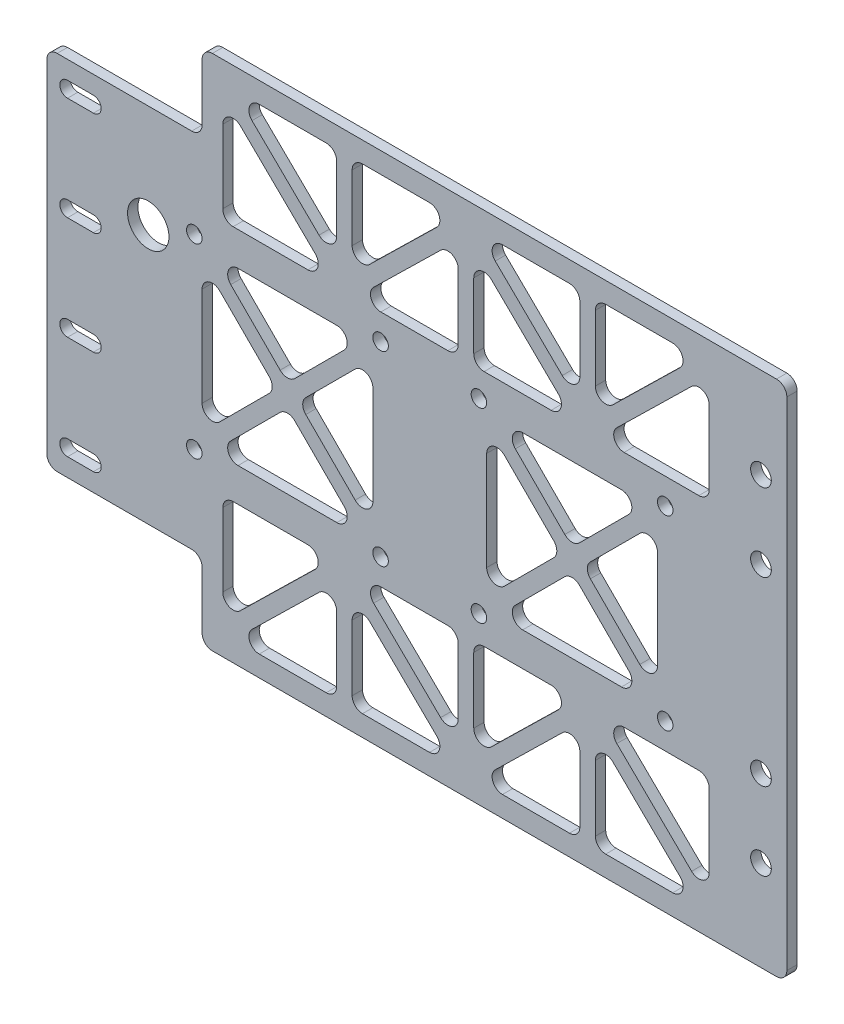
SolidWorks part; units mm, degrees
material "Thornel Mat VMA"
ref_plane "前视基准面" through (0, 0, 0) normal (0, 0, 1) x (1, 0, 0)
ref_plane "上视基准面" through (0, 0, 0) normal (0, 1, 0) x (1, 0, 0)
ref_plane "右视基准面" through (0, 0, 0) normal (1, 0, 0) x (0, 0, -1)
other "Configuration Table"
sketch "草图1" plane through (0, 0, 0) normal (0, 0, 1) x (1, 0, 0)
  line L1 (-71.5, -50) -> (71.5, -50)
  line L2 (-71.5, -50) -> (-71.5, 50)
  line L3 (-71.5, 50) -> (71.5, 50)
  line L4 (71.5, -50) -> (71.5, 50)
  line L5 (-71.5, -50) -> (71.5, 50) construction
  line L6 (-71.5, 50) -> (71.5, -50) construction
  point P0 (0, 0)
  dimension "D1" = 100
  dimension "D2" = 143
extrude "凸台-拉伸1" add sketch "草图1" along normal blind 2
sketch "草图2" plane through (0, 0, 2) normal (0, 0, 1) x (1, 0, 0)
  line L0 (66.5, 50) -> (66.5, 32.5) construction
  line L1 (71.5, 50) -> (-71.5, 50) construction
  line L2 (66.5, 32.5) -> (66.5, 17.5) construction
  line L3 (0, 0) -> (86.4938, 0) construction
  line L4 (71.5, -50) -> (71.5, 50) construction
  line L5 (66.5, -32.5) -> (66.5, -17.5) construction
  line L6 (0, 0) -> (-95.2784, 0) construction
  line L7 (-67.5, 50) -> (-67.5, 30) construction
  line L8 (-67.5, 30) -> (-67.5, 10) construction
  line L9 (-67.5, 10) -> (-62.5, 10) construction
  line L10 (-67.5, 11.5) -> (-62.5, 11.5)
  line L11 (-67.5, 8.5) -> (-62.5, 8.5)
  line L12 (-71.5, 50) -> (-71.5, -50) construction
  line L13 (-67.5, 30) -> (-62.5, 30) construction
  line L14 (-67.5, 31.5) -> (-62.5, 31.5)
  line L15 (-67.5, 28.5) -> (-62.5, 28.5)
  line L16 (-67.5, -30) -> (-67.5, -10) construction
  line L17 (-67.5, -30) -> (-62.5, -30) construction
  line L18 (-67.5, -31.5) -> (-62.5, -31.5)
  line L19 (-67.5, -28.5) -> (-62.5, -28.5)
  line L20 (-67.5, -10) -> (-62.5, -10) construction
  line L21 (-67.5, -11.5) -> (-62.5, -11.5)
  line L22 (-67.5, -8.5) -> (-62.5, -8.5)
  circle A0 centre (66.5, 32.5) radius 2
  circle A1 centre (66.5, 17.5) radius 2
  circle A2 centre (66.5, -17.5) radius 2
  circle A3 centre (66.5, -32.5) radius 2
  arc A4 (-67.5, 11.5) -> (-67.5, 8.5) centre (-67.5, 10) ccw
  arc A5 (-62.5, 8.5) -> (-62.5, 11.5) centre (-62.5, 10) ccw
  arc A6 (-67.5, 31.5) -> (-67.5, 28.5) centre (-67.5, 30) ccw
  arc A7 (-62.5, 28.5) -> (-62.5, 31.5) centre (-62.5, 30) ccw
  arc A8 (-67.5, -31.5) -> (-67.5, -28.5) centre (-67.5, -30) cw
  arc A9 (-62.5, -28.5) -> (-62.5, -31.5) centre (-62.5, -30) cw
  arc A10 (-67.5, -11.5) -> (-67.5, -8.5) centre (-67.5, -10) cw
  arc A11 (-62.5, -8.5) -> (-62.5, -11.5) centre (-62.5, -10) cw
  point P19 (-65, 10)
  point P28 (-65, 30)
  point P37 (-65, -30)
  point P43 (-65, -10)
  dimension "D4" = 4
  dimension "D7" = 1.5
  dimension "D1" = 17.5
  dimension "D2" = 15
  dimension "D3" = 5
  dimension "D5" = 20
  dimension "D6" = 10
  dimension "D8" = 5
  dimension "D9" = 4
  dimension "D10" = 5
extrude "切除-拉伸1" cut sketch "草图2" against normal up to surface (2 mm away) up to face at (0, 0, 0)
sketch "草图3" plane through (0, 0, 2) normal (0, 0, 1) x (1, 0, 0)
  line L0 (0, 0) -> (30, 0) construction
  line L1 (0, 0) -> (-25, 0) construction
  line L3 (12, -18) -> (48, -18) construction
  line L4 (12, -18) -> (12, 18) construction
  line L5 (12, 18) -> (48, 18) construction
  line L6 (48, -18) -> (48, 18) construction
  line L7 (12, -18) -> (48, 18) construction
  line L8 (12, 18) -> (48, -18) construction
  line L9 (-43, -18) -> (-7, -18) construction
  line L10 (-43, -18) -> (-43, 18) construction
  line L11 (-43, 18) -> (-7, 18) construction
  line L12 (-7, -18) -> (-7, 18) construction
  line L13 (-43, -18) -> (-7, 18) construction
  line L14 (-43, 18) -> (-7, -18) construction
  circle A0 centre (66.5, -17.5) radius 2 construction
  circle A1 centre (48, 18) radius 1.5
  circle A2 centre (48, -18) radius 1.5
  circle A3 centre (12, -18) radius 1.5
  circle A4 centre (12, 18) radius 1.5
  circle A5 centre (-7, 18) radius 1.5
  circle A6 centre (-7, -18) radius 1.5
  circle A7 centre (-43, -18) radius 1.5
  circle A8 centre (-43, 18) radius 1.5
  dimension "D4" = 3
  dimension "D1" = 18.5
  dimension "D2" = 19
  dimension "D3" = 36
extrude "切除-拉伸2" cut sketch "草图3" against normal up to surface (2 mm away) up to face at (-65, 10, 0)
sketch "草图4" plane through (0, 0, 2) normal (0, 0, 1) x (1, 0, 0)
  line L1 (-71.5, 50) -> (-41.5, 50)
  line L2 (-71.5, 50) -> (-71.5, 35)
  line L3 (-71.5, 35) -> (-41.5, 35)
  line L4 (-41.5, 50) -> (-41.5, 35)
  line L5 (-71.5, -50) -> (-41.5, -50)
  line L6 (-71.5, -50) -> (-71.5, -35)
  line L7 (-71.5, -35) -> (-41.5, -35)
  line L8 (-41.5, -50) -> (-41.5, -35)
  dimension "D1" = 30
  dimension "D2" = 15
extrude "切除-拉伸3" cut sketch "草图4" against normal up to surface (2 mm away) up to face at (46.5, -18, 0)
sketch "草图5" plane through (0, 0, 2) normal (0, 0, 1) x (1, 0, 0)
  line L0 (-43, 18) -> (-7, -18) construction
  line L1 (-7, -18) -> (-43, -18) construction
  line L2 (-43, -18) -> (-7, 18) construction
  line L3 (-7, 18) -> (-43, 18) construction
  line L4 (0, 0) -> (98.3123, 0) construction
  line L5 (-37.5, 46) -> (56.5, 46)
  line L6 (-37.5, 46) -> (-37.5, 23)
  line L7 (-37.5, 23) -> (56.5, 23)
  line L8 (56.5, 46) -> (56.5, 23)
  line L9 (-39.3787, 16.5) -> (-25, 2.1213)
  line L10 (-25, 2.1213) -> (-10.6213, 16.5)
  line L11 (-10.6213, 16.5) -> (-39.3787, 16.5)
  line L12 (-41.5, 35) -> (-41.5, 50) construction
  line L13 (71.5, 50) -> (-41.5, 50) construction
  line L14 (71.5, -50) -> (71.5, 50) construction
  line L15 (56.5, 46) -> (33, 23) construction
  line L16 (33, 23) -> (9.5, 46) construction
  line L17 (9.5, 46) -> (-14, 23) construction
  line L18 (-14, 23) -> (-37.5, 46) construction
  line L19 (-37.5, 43.9011) -> (-16.1445, 23)
  line L20 (-35.3555, 46) -> (-14, 25.0989)
  line L21 (-14, 25.0989) -> (7.3555, 46)
  line L22 (-11.8555, 23) -> (9.5, 43.9011)
  line L23 (9.5, 43.9011) -> (30.8555, 23)
  line L24 (11.6445, 46) -> (33, 25.0989)
  line L25 (33, 25.0989) -> (54.3555, 46)
  line L26 (35.1445, 23) -> (56.5, 43.9011)
  line L27 (-15.5, 23) -> (-15.5, 46)
  line L28 (-14, 23) -> (-14, 46) construction
  line L29 (-12.5, 23) -> (-12.5, 46)
  line L30 (9.5, 46) -> (9.5, 23) construction
  line L31 (8, 46) -> (8, 23)
  line L32 (11, 46) -> (11, 23)
  line L33 (34.5, 23) -> (34.5, 46)
  line L34 (31.5, 23) -> (31.5, 46)
  line L35 (-41.5, -14.3787) -> (-41.5, 14.3787)
  line L36 (-41.5, 14.3787) -> (-27.1213, 0)
  line L37 (-27.1213, 0) -> (-41.5, -14.3787)
  line L38 (-25, -2.1213) -> (-39.3787, -16.5)
  line L39 (-39.3787, -16.5) -> (-10.6213, -16.5)
  line L40 (-8.5, -14.3787) -> (-22.8787, 0)
  line L41 (-10.6213, -16.5) -> (-25, -2.1213)
  line L42 (-22.8787, 0) -> (-8.5, 14.3787)
  line L43 (-8.5, 14.3787) -> (-8.5, -14.3787)
  line L44 (-7, 18) -> (12, 18) construction
  line L45 (2.5, 18) -> (2.5, -26.3932) construction
  line L46 (48, -18) -> (12, 18) construction
  line L47 (12, -18) -> (48, -18) construction
  line L48 (13.5, 14.3787) -> (13.5, -14.3787)
  line L49 (27.8787, 0) -> (13.5, 14.3787)
  line L50 (15.6213, -16.5) -> (30, -2.1213)
  line L51 (13.5, -14.3787) -> (27.8787, 0)
  line L52 (44.3787, -16.5) -> (15.6213, -16.5)
  line L53 (30, -2.1213) -> (44.3787, -16.5)
  line L54 (32.1213, 0) -> (46.5, -14.3787)
  line L55 (46.5, 14.3787) -> (32.1213, 0)
  line L56 (46.5, -14.3787) -> (46.5, 14.3787)
  line L57 (15.6213, 16.5) -> (44.3787, 16.5)
  line L58 (30, 2.1213) -> (15.6213, 16.5)
  line L59 (44.3787, 16.5) -> (30, 2.1213)
  line L60 (9.5, -46) -> (9.5, -23) construction
  line L61 (-14, -23) -> (-14, -46) construction
  line L62 (-14, -23) -> (-37.5, -46) construction
  line L63 (9.5, -46) -> (-14, -23) construction
  line L64 (33, -23) -> (9.5, -46) construction
  line L65 (56.5, -46) -> (33, -23) construction
  line L66 (31.5, -23) -> (31.5, -46)
  line L67 (34.5, -23) -> (34.5, -46)
  line L68 (11, -46) -> (11, -23)
  line L69 (8, -46) -> (8, -23)
  line L70 (-12.5, -23) -> (-12.5, -46)
  line L71 (-15.5, -23) -> (-15.5, -46)
  line L72 (35.1445, -23) -> (56.5, -43.9011)
  line L73 (33, -25.0989) -> (54.3555, -46)
  line L74 (11.6445, -46) -> (33, -25.0989)
  line L75 (9.5, -43.9011) -> (30.8555, -23)
  line L76 (-11.8555, -23) -> (9.5, -43.9011)
  line L77 (-14, -25.0989) -> (7.3555, -46)
  line L78 (-35.3555, -46) -> (-14, -25.0989)
  line L79 (-37.5, -43.9011) -> (-16.1445, -23)
  line L80 (56.5, -46) -> (56.5, -23)
  line L81 (-37.5, -23) -> (56.5, -23)
  line L82 (-37.5, -46) -> (-37.5, -23)
  line L83 (-37.5, -46) -> (56.5, -46)
  circle A0 centre (-7, 18) radius 1.5 construction
  dimension "D1" = 1.5
  dimension "D2" = 1.5
  dimension "D3" = 1.5
  dimension "D4" = 4
  dimension "D5" = 4
  dimension "D6" = 15
  dimension "D7" = 5
  dimension "D8" = 1.5
  dimension "D9" = 1.5
  dimension "D10" = 1.5
  dimension "D11" = 3
  dimension "D12" = 1.5
  dimension "D13" = 1.5
  dimension "D14" = 1.5
  dimension "D15" = 1.5
  dimension "D16" = 1.5
extrude "切除-拉伸4" cut sketch "草图5" against normal blind 2 contours L37 L36 L35 | L10 L11 L9 | L43 L42 L40 | L39 L41 L38 | L48 L51 L49 | L59 L57 L58 | L54 L56 L55 | L53 L50 L52 | L81 L72 L80 | L67 L83 L73 | L74 L83 L66 | L81 L68 L75 | L81 L76 L69 | L70 L83 L77 | L78 L83 L71 | L82 L79 L81 | L19 L6 L7 | L20 L27 L5 | L29 L21 L5 | L31 L22 L7 | L23 L32 L7 | L24 L34 L5 | L33 L25 L5 | L26 L7 L8
sketch "草图6" plane through (0, 0, 2) normal (0, 0, 1) x (1, 0, 0)
  line L1 (-71.5, 35) -> (-41.5, 35) construction
  line L2 (-71.5, 35) -> (-71.5, -35) construction
  circle A0 centre (-51.9, 15.1) radius 4
  dimension "D2" = 8
  dimension "D1" = 19.9
  dimension "D3" = 19.6
extrude "切除-拉伸5" cut sketch "草图6" against normal blind 10
fillet "圆角1" radius 2 80 edges at (8, -42.433, 1) (-11.8555, -23, 1) (8, -23, 1) (11, -42.433, 1) (11, -23, 1) (30.8555, -23, 1) (31.5, -46, 1) (11.6445, -46, 1) (31.5, -26.567, 1) (-37.5, 43.9011, 1) (-16.1445, 23, 1) (-16.1445, -23, 1) (-37.5, -43.9011, 1) (-37.5, -23, 1) (-15.5, -46, 1) (-35.3555, -46, 1) (-15.5, -26.567, 1) (-22.8787, 0, 1) (-8.5, 14.3787, 1) (-8.5, -14.3787, 1) (56.5, -43.9011, 1) (35.1445, -23, 1) (56.5, -23, 1) (15.6213, -16.5, 1) (30, -2.1213, 1) (44.3787, -16.5, 1) (15.6213, 16.5, 1) (44.3787, 16.5, 1) (30, 2.1213, 1) (54.3555, 46, 1) (34.5, 26.567, 1) (34.5, 46, 1) (56.5, 23, 1) (35.1445, 23, 1) (56.5, 43.9011, 1) (7.3555, 46, 1) (-12.5, 26.567, 1) (-12.5, 46, 1) (-11.8555, 23, 1) (8, 42.433, 1) (8, 23, 1) (11, 23, 1) (11, 42.433, 1) (30.8555, 23, 1) (-41.5, 14.3787, 1) (-27.1213, 0, 1) (-41.5, -14.3787, 1) (-71.5, 35, 1) (-71.5, -35, 1) (-41.5, -35, 1) (-41.5, -50, 1) (71.5, -50, 1) (71.5, 50, 1) (-41.5, 50, 1) (-41.5, 35, 1) (-35.3555, 46, 1) (-15.5, 46, 1) (-15.5, 26.567, 1) (11.6445, 46, 1) (31.5, 46, 1) (31.5, 26.567, 1) (32.1213, 0, 1) (46.5, 14.3787, 1) (46.5, -14.3787, 1) (-25, 2.1213, 1) (-39.3787, 16.5, 1) (-10.6213, 16.5, 1) (-39.3787, -16.5, 1) (-25, -2.1213, 1) (-10.6213, -16.5, 1) (13.5, 14.3787, 1) (27.8787, 0, 1) (13.5, -14.3787, 1) (-12.5, -26.567, 1) (7.3555, -46, 1) (-12.5, -46, 1) (34.5, -26.567, 1) (54.3555, -46, 1) (34.5, -46, 1) (-37.5, 23, 1)
